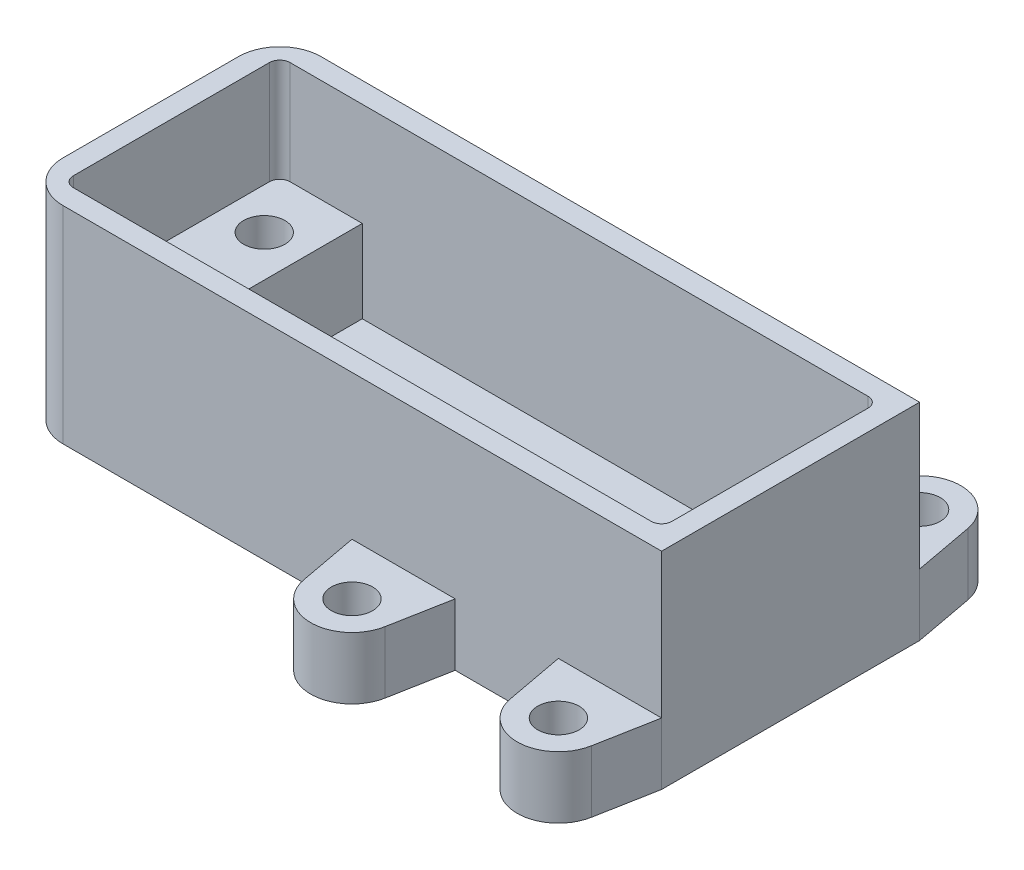
SolidWorks part; units mm, degrees
ref_plane "前视基准面" through (0, 0, 0) normal (0, 0, 1) x (1, 0, 0)
ref_plane "上视基准面" through (0, 0, 0) normal (0, 1, 0) x (1, 0, 0)
ref_plane "右视基准面" through (0, 0, 0) normal (1, 0, 0) x (0, 0, -1)
sketch "草图1" plane through (0, 0, 0) normal (0, 1, 0) x (1, 0, 0)
  line L1 (-31, -12.5) -> (31, -12.5)
  line L2 (-31, -12.5) -> (-31, 12.5)
  line L3 (-31, 12.5) -> (31, 12.5)
  line L4 (31, -12.5) -> (31, 12.5)
  line L5 (-31, -12.5) -> (31, 12.5) construction
  line L6 (-31, 12.5) -> (31, -12.5) construction
  point P0 (0, 0)
  dimension "D1" = 62
  dimension "D2" = 25
extrude "凸台-拉伸1" add sketch "草图1" along normal blind 20
shell "抽壳1" thickness 2
sketch "草图2" plane through (0, 2, 0) normal (0, 1, 0) x (1, 0, 0)
  line L0 (-29, -10.5) -> (29, -10.5) construction
  line L1 (-29, 10.5) -> (-21, 10.5)
  line L2 (-29, 10.5) -> (-29, -10.5)
  line L3 (-29, -10.5) -> (-21, -10.5)
  line L4 (-21, 10.5) -> (-21, -10.5)
  line L5 (29, 10.5) -> (-29, 10.5) construction
  line L6 (21, 10.5) -> (29, 10.5)
  line L7 (21, 10.5) -> (21, -10.5)
  line L8 (21, -10.5) -> (29, -10.5)
  line L9 (29, 10.5) -> (29, -10.5)
  dimension "D1" = 8
  dimension "D2" = 8
extrude "凸台-拉伸2" add sketch "草图2" along normal blind 8
sketch "草图3" plane through (0, 10, 0) normal (0, 1, 0) x (1, 0, 0)
  line L2 (29, -10.5) -> (29, 10.5) construction
  line L3 (29, 10.5) -> (21, 10.5) construction
  line L4 (0, 0) -> (0, 14.9506) construction
  circle A0 centre (25, 5) radius 2
  circle A1 centre (25, -5) radius 2
  circle A2 centre (-25, -5) radius 2
  circle A3 centre (-25, 5) radius 2
  circle A4 centre (-25, -5) radius 2
  circle A5 centre (-25, 5) radius 2
  dimension "D1" = 4
  dimension "D2" = 4
  dimension "D3" = 5.5
  dimension "D4" = 10
extrude "切除-拉伸1" cut sketch "草图3" against normal through all contours A3 | A2 | A0 | A1
sketch "草图4" plane through (0, 2, 0) normal (0, 1, 0) x (1, 0, 0)
  line L0 (-21, -10.5) -> (-21, 10.5) construction
  circle A0 centre (-12, 0) radius 6
  dimension "D1" = 9
  dimension "D2" = 12
extrude "切除-拉伸2" cut sketch "草图4" against normal through all
sketch "草图5" plane through (0, 0, 0) normal (0, 1, 0) x (1, 0, 0)
  line L0 (22.0676, 18.2324) -> (21, 12.5)
  line L1 (31, 12.5) -> (-31, 12.5) construction
  line L2 (21, 12.5) -> (31, 12.5)
  line L3 (31, 12.5) -> (29.9324, 18.2324)
  line L4 (26, 17.5) -> (26, 12.5) construction
  line L5 (2.0676, 18.2324) -> (1, 12.5)
  line L6 (11, 12.5) -> (9.9324, 18.2324)
  line L7 (1, 12.5) -> (11, 12.5)
  arc A0 (29.9324, 18.2324) -> (22.0676, 18.2324) centre (26, 17.5) ccw
  circle A1 centre (26, 17.5) radius 2
  arc A2 (9.9324, 18.2324) -> (2.0676, 18.2324) centre (6, 17.5) ccw
  circle A3 centre (6, 17.5) radius 2
  dimension "D3" = 4
  dimension "D4" = 4
  dimension "D6" = 20
  dimension "D1" = 5
  dimension "D2" = 5
  dimension "D5" = 2
extrude "凸台-拉伸3" add sketch "草图5" along normal blind 6
mirror "镜向1" about plane through (0, 0, 0) normal (0, 0, 1) of "凸台-拉伸3"
fillet "圆角1" radius 4 2 edges at (-31, 10, -12.5) (-31, 10, 12.5)
fillet "圆角2" radius 1 4 edges at (29, 15, -10.5) (-29, 15, 10.5) (29, 15, 10.5) (-29, 15, -10.5)
move or copy body "实体-移动/复制1" [suppressed] bodies to move or copy 111
